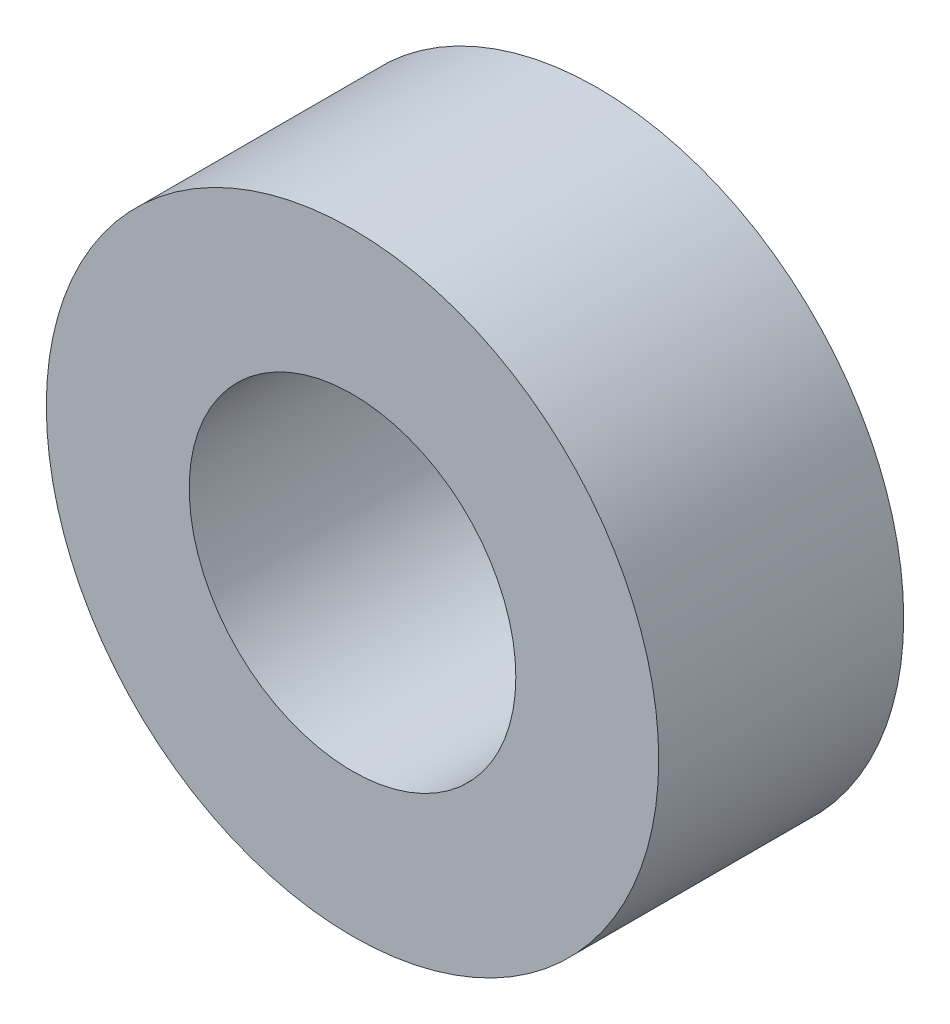
SolidWorks part; units mm, degrees
ref_plane "Front Plane" through (0, 0, 0) normal (0, 0, 1) x (1, 0, 0)
ref_plane "Top Plane" through (0, 0, 0) normal (0, 1, 0) x (1, 0, 0)
ref_plane "Right Plane" through (0, 0, 0) normal (1, 0, 0) x (0, 0, -1)
sketch "草圖1" plane through (0, 0, 0) normal (0, 0, 1) x (1, 0, 0)
  circle A0 centre (0, 0) radius 3
  circle A1 centre (0, 0) radius 1.6
extrude "填料-伸長1" add sketch "草圖1" along normal blind 2.4
